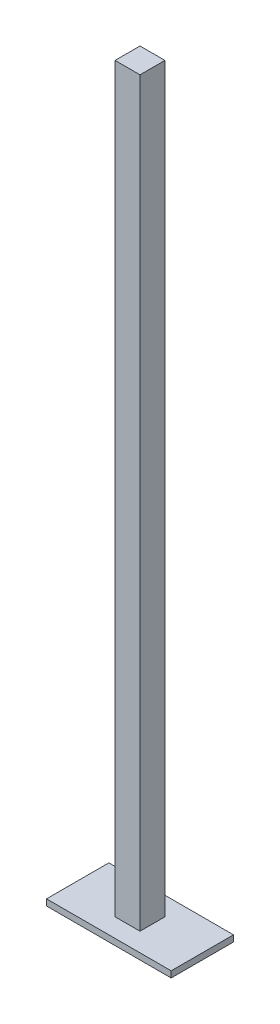
SolidWorks part; units mm, degrees
ref_plane "Front Plane" through (0, 0, 0) normal (0, 0, 1) x (1, 0, 0)
ref_plane "Top Plane" through (0, 0, 0) normal (0, 1, 0) x (1, 0, 0)
ref_plane "Right Plane" through (0, 0, 0) normal (1, 0, 0) x (0, 0, -1)
sketch "Sketch1" plane through (0, 0, 0) normal (0, 1, 0) x (1, 0, 0)
  line L1 (-50, 25) -> (50, 25)
  line L2 (-50, 25) -> (-50, -25)
  line L3 (-50, -25) -> (50, -25)
  line L4 (50, 25) -> (50, -25)
  dimension "D1" = 100
  dimension "D2" = 50
  dimension "D3" = 25
  dimension "D4" = 50
extrude "Extrude1" add sketch "Sketch1" along normal blind 5
sketch "Sketch2" plane through (0, 0, 0) normal (0, 1, 0) x (1, 0, 0)
  line L1 (-10, -10) -> (10, -10)
  line L2 (-10, -10) -> (-10, 10)
  line L3 (-10, 10) -> (10, 10)
  line L4 (10, -10) -> (10, 10)
  dimension "D1" = 20
  dimension "D2" = 20
  dimension "D3" = 10
  dimension "D4" = 10
extrude "Extrude2" add sketch "Sketch2" along normal blind 600
